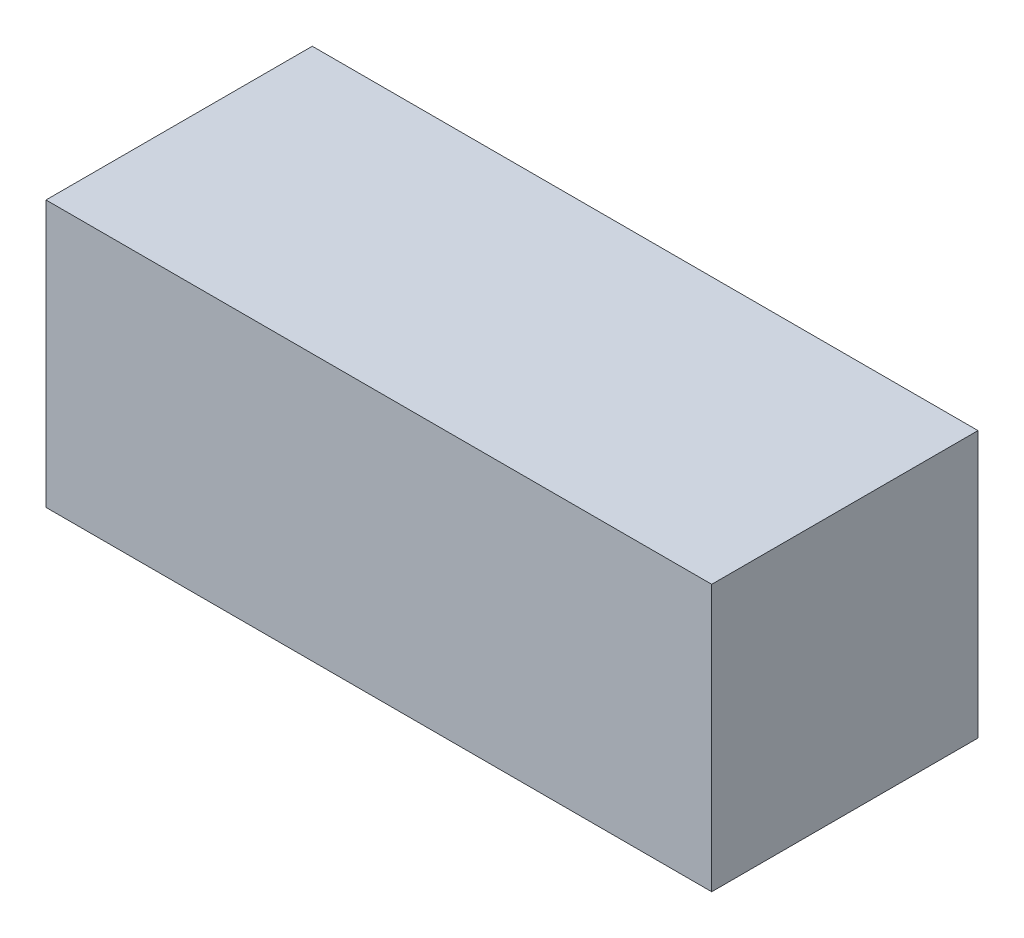
SolidWorks part; units mm, degrees
ref_plane "정면" through (0, 0, 0) normal (0, 0, 1) x (1, 0, 0)
ref_plane "윗면" through (0, 0, 0) normal (0, 1, 0) x (1, 0, 0)
ref_plane "우측면" through (0, 0, 0) normal (1, 0, 0) x (0, 0, -1)
sketch "스케치1" plane through (0, 0, 0) normal (0, 1, 0) x (1, 0, 0)
  line L1 (-25, -10) -> (25, -10)
  line L2 (-25, -10) -> (-25, 10)
  line L3 (-25, 10) -> (25, 10)
  line L4 (25, -10) -> (25, 10)
  line L5 (-25, -10) -> (25, 10) construction
  line L6 (-25, 10) -> (25, -10) construction
  point P0 (0, 0)
extrude "보스-돌출1" add sketch "스케치1" along normal blind 20
